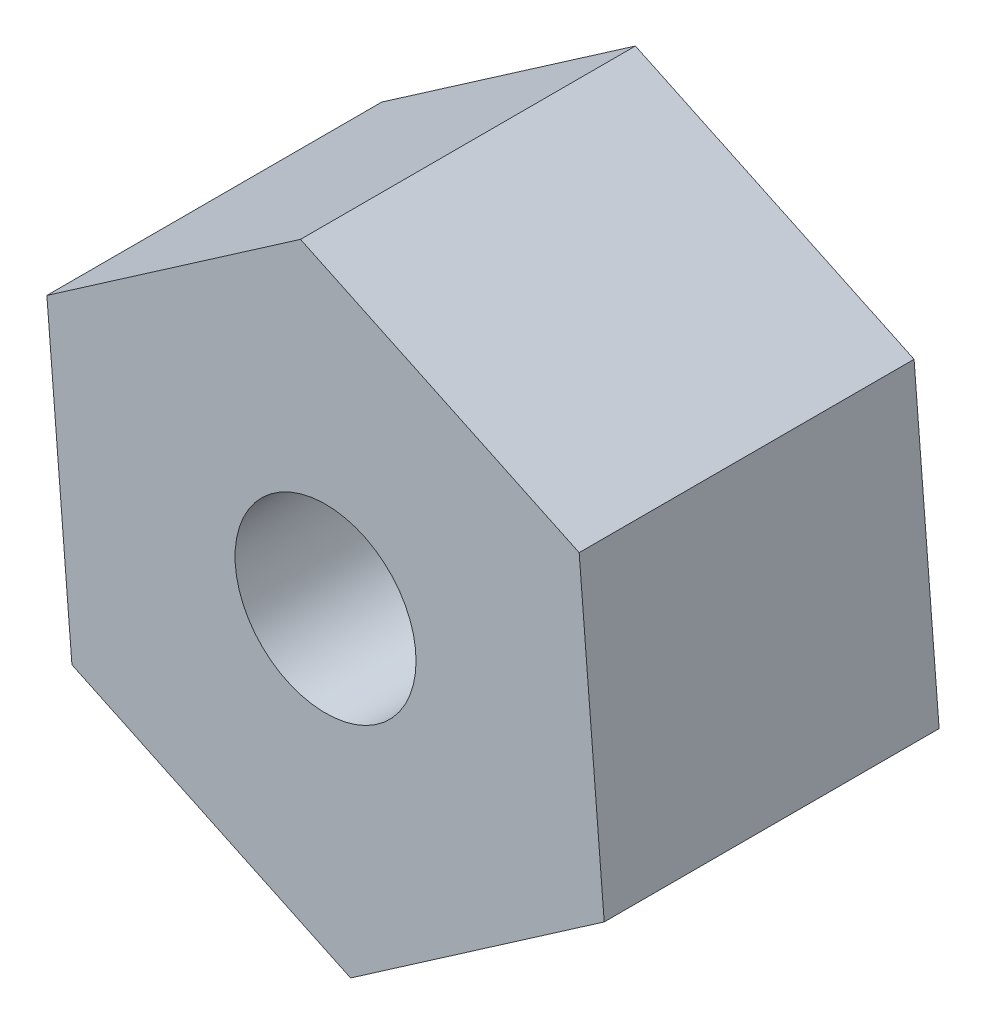
SolidWorks part; units mm, degrees
ref_plane "Plan de face" through (0, 0, 0) normal (0, 0, 1) x (1, 0, 0)
ref_plane "Plan de dessus" through (0, 0, 0) normal (0, 1, 0) x (1, 0, 0)
ref_plane "Plan de droite" through (0, 0, 0) normal (1, 0, 0) x (0, 0, -1)
sketch "Esquisse1" plane through (0, 0, 0) normal (0, 0, 1) x (1, 0, 0)
  line L1 (-0.2767, 3.3951) -> (-3.0786, 1.4579)
  line L2 (-3.0786, 1.4579) -> (-2.8019, -1.9372)
  line L3 (-2.8019, -1.9372) -> (0.2767, -3.3951)
  line L4 (0.2767, -3.3951) -> (3.0786, -1.4579)
  line L5 (3.0786, -1.4579) -> (2.8019, 1.9372)
  line L6 (2.8019, 1.9372) -> (-0.2767, 3.3951)
  circle A0 centre (0, 0) radius 1
  circle A1 centre (0, 0) radius 2.95 construction
  dimension "D1" = 2
  dimension "D2" = 5.9
extrude "Boss.-Extru.1" add sketch "Esquisse1" along normal blind 3.7
cosmetic thread "Représentation de filetage1" parameters "D2"=2.5
